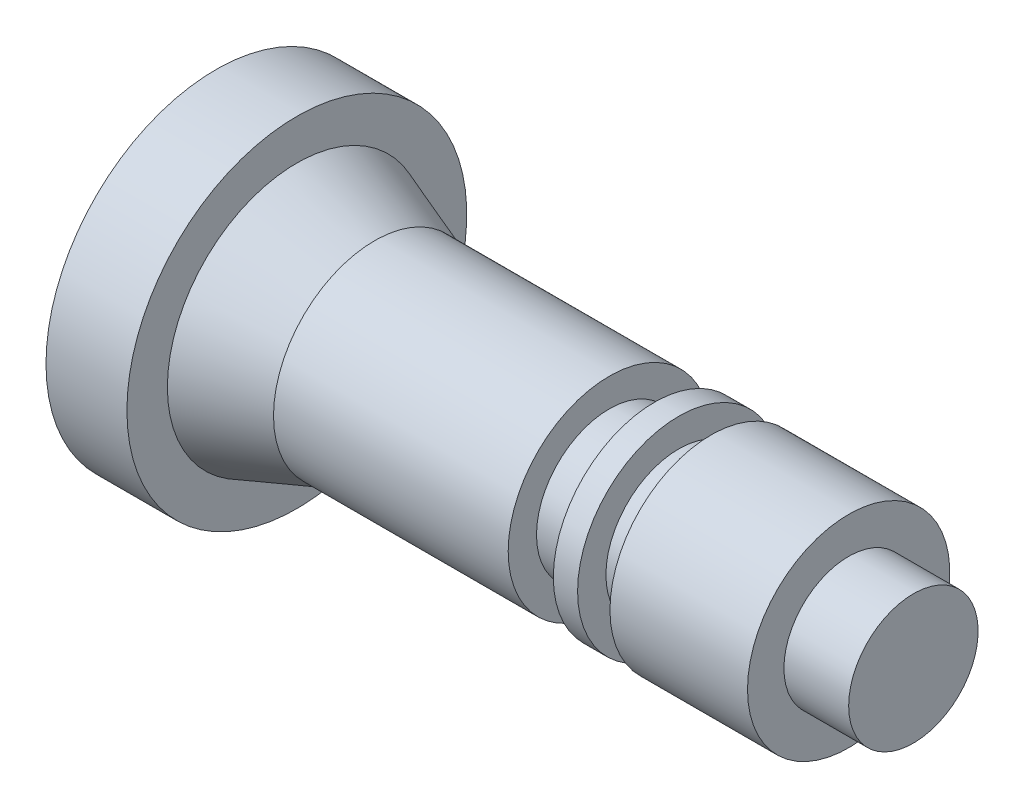
SolidWorks part; units mm, degrees
ref_plane "Front Plane" through (0, 0, 0) normal (0, 0, 1) x (1, 0, 0)
ref_plane "Top Plane" through (0, 0, 0) normal (0, 1, 0) x (1, 0, 0)
ref_plane "Right Plane" through (0, 0, 0) normal (1, 0, 0) x (0, 0, -1)
sketch "Sketch1" plane through (0, 0, 0) normal (0, 0, 1) x (1, 0, 0)
  line L0 (0, 0) -> (86.197, 0) construction
  line L1 (0, 0) -> (0, 21)
  line L2 (0, 21) -> (10, 21)
  line L3 (10, 21) -> (10, 16)
  line L4 (10, 16) -> (19.6162, 12.5)
  line L5 (19.6162, 12.5) -> (48.6195, 12.5)
  line L6 (48.6195, 12.5) -> (48.6195, 9)
  line L7 (48.6195, 9) -> (54.197, 9)
  line L8 (54.197, 9) -> (54.197, 12.5)
  line L9 (61.197, 9) -> (61.197, 12.5)
  line L10 (54.197, 12.5) -> (57.197, 12.5)
  line L11 (57.197, 9) -> (61.197, 9)
  line L12 (61.197, 12.5) -> (78.197, 12.5)
  line L13 (0, 0) -> (86.197, 0)
  line L14 (78.197, 12.5) -> (78.197, 8)
  line L15 (78.197, 8) -> (86.197, 8)
  line L16 (86.197, 8) -> (86.197, 0)
  line L17 (57.197, 12.5) -> (57.197, 9)
  dimension "D1" = 21
  dimension "D2" = 10
  dimension "D3" = 16
  dimension "D4" = 12.5
  dimension "D5" = 160
  dimension "D6" = 9
  dimension "D7" = 4
  dimension "D8" = 8
  dimension "D9" = 8
  dimension "D10" = 25
  dimension "D11" = 32
  dimension "D12" = 12.5
revolve "Revolve1" add sketch "Sketch1" angle 360 about L0
